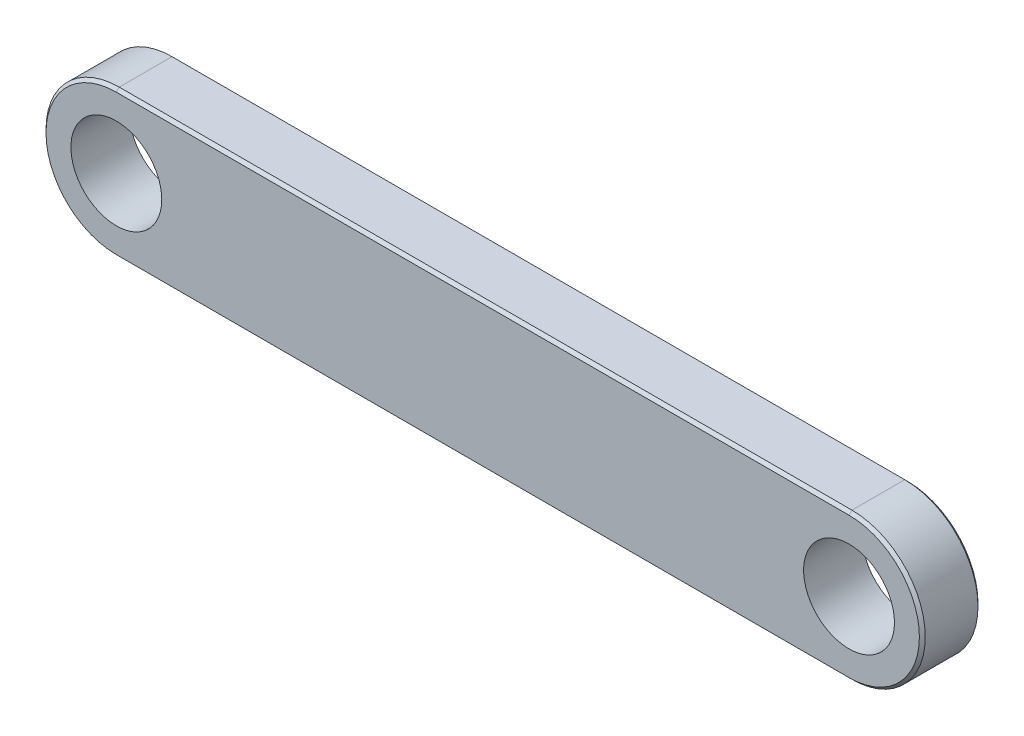
SolidWorks part; units mm, degrees
ref_plane "Front Plane" through (0, 0, 0) normal (0, 0, 1) x (1, 0, 0)
ref_plane "Top Plane" through (0, 0, 0) normal (0, 1, 0) x (1, 0, 0)
ref_plane "Right Plane" through (0, 0, 0) normal (1, 0, 0) x (0, 0, -1)
sketch "Sketch2" plane through (0, 0, 0) normal (0, 0, 1) x (1, 0, 0)
  line L0 (-12.5, 0) -> (12.5, 0) construction
  line L1 (-12.5, 2.5) -> (12.5, 2.5)
  line L2 (-12.5, -2.5) -> (12.5, -2.5)
  arc A0 (-12.5, 2.5) -> (-12.5, -2.5) centre (-12.5, 0) ccw
  arc A1 (12.5, -2.5) -> (12.5, 2.5) centre (12.5, 0) ccw
  circle A2 centre (-12.5, 0) radius 1.55
  circle A3 centre (12.5, 0) radius 1.55
  point P2 (0, 0)
  dimension "D2" = 2.5
  dimension "D3" = 3.1
  dimension "D1" = 25
extrude "Boss-Extrude1" add sketch "Sketch2" along normal blind 2
chamfer "Chamfer1" distance 0.1 angle 45 8 edges at (15, 0, 0) (0, -2.5, 0) (-15, 0, 0) (0, 2.5, 0) (0, -2.5, 2) (-15, 0, 2) (15, 0, 2) (0, 2.5, 2)
